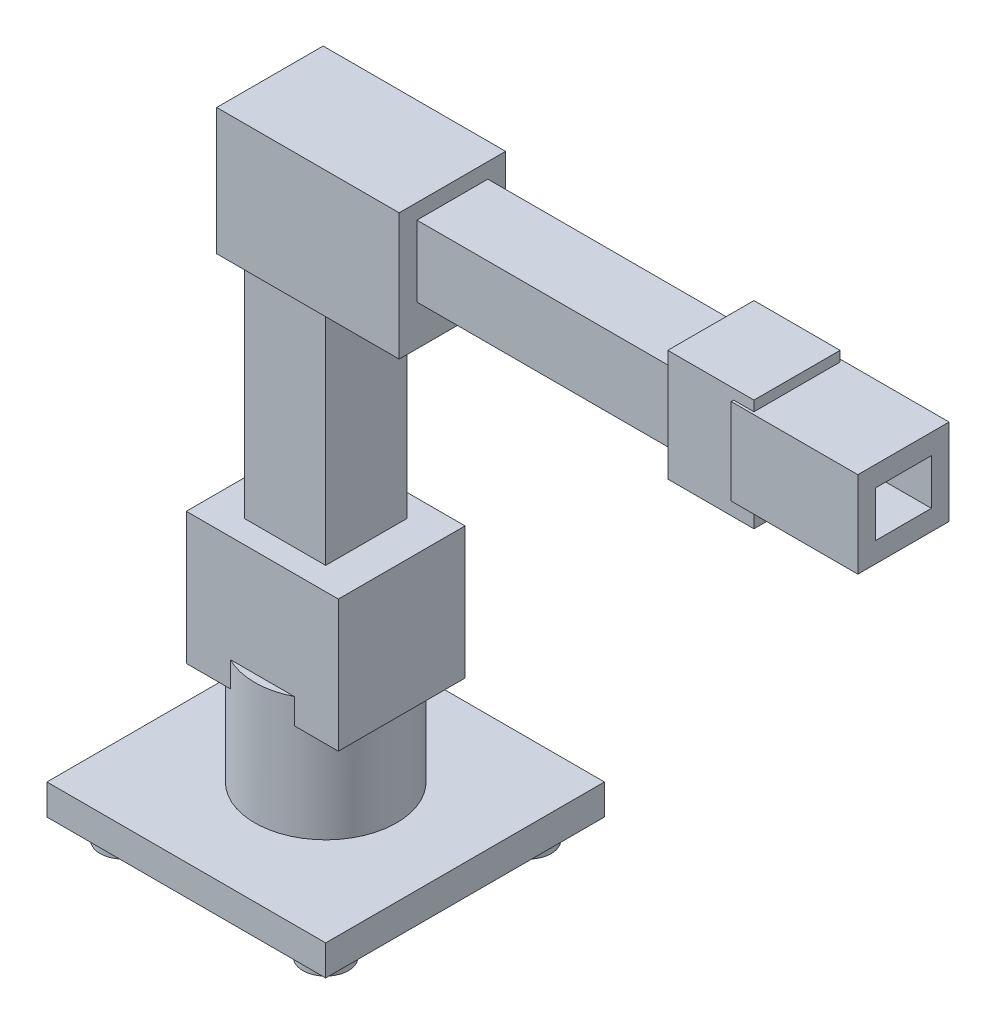
SolidWorks part; units mm, degrees
ref_plane "Front Plane" through (0, 0, 0) normal (0, 0, 1) x (1, 0, 0)
ref_plane "Top Plane" through (0, 0, 0) normal (0, 1, 0) x (1, 0, 0)
ref_plane "Right Plane" through (0, 0, 0) normal (1, 0, 0) x (0, 0, -1)
sketch "Sketch1" plane through (0, 0, 0) normal (0, 1, 0) x (1, 0, 0)
  line L1 (-55, -55) -> (55, -55)
  line L2 (-55, -55) -> (-55, 55)
  line L3 (-55, 55) -> (55, 55)
  line L4 (55, -55) -> (55, 55)
extrude "Boss-Extrude1" add sketch "Sketch1" along normal blind 12
sketch "Sketch2" plane through (0, 0, 0) normal (0, 1, 0) x (1, 0, 0)
  circle A0 centre (-40, -40) radius 9
  circle A1 centre (40, -40) radius 9
  circle A2 centre (-40, 40) radius 9
  circle A3 centre (40, 40) radius 9
extrude "Boss-Extrude2" add sketch "Sketch2" against normal blind 8
sketch "Sketch3" plane through (0, 0, 0) normal (0, 1, 0) x (1, 0, 0)
  circle A0 centre (0, 0) radius 28
extrude "Boss-Extrude3" add sketch "Sketch3" along normal blind 60
sketch "Sketch4" plane through (0, 0, 0) normal (0, 0, 1) x (1, 0, 0)
  line L1 (-30, 50) -> (30, 50)
  line L2 (-30, 50) -> (-30, 102)
  line L3 (-30, 102) -> (30, 102)
  line L4 (30, 50) -> (30, 102)
extrude "Boss-Extrude4" add sketch "Sketch4" along normal mid plane 50
sketch "Sketch5" plane through (0, 0, 0) normal (0, 0, 1) x (1, 0, 0)
  line L1 (-16, 98) -> (16, 98)
  line L2 (-16, 98) -> (-16, 205)
  line L3 (-16, 205) -> (16, 205)
  line L4 (16, 98) -> (16, 205)
extrude "Boss-Extrude5" add sketch "Sketch5" along normal mid plane 32
sketch "Sketch6" plane through (0, 0, 0) normal (0, 0, 1) x (1, 0, 0)
  line L1 (-22, 192) -> (50, 192)
  line L2 (-22, 192) -> (-22, 242)
  line L3 (-22, 242) -> (50, 242)
  line L4 (50, 192) -> (50, 242)
extrude "Boss-Extrude6" add sketch "Sketch6" along normal mid plane 42
sketch "Sketch7" plane through (0, 0, 0) normal (0, 0, 1) x (1, 0, 0)
  circle A0 centre (14, 217) radius 18
extrude "Boss-Extrude7" add sketch "Sketch7" along normal mid plane 12
sketch "Sketch8" plane through (0, 0, 0) normal (0, 0, 1) x (1, 0, 0)
  line L1 (45, 208) -> (160, 208)
  line L2 (45, 208) -> (45, 236)
  line L3 (45, 236) -> (160, 236)
  line L4 (160, 208) -> (160, 236)
extrude "Boss-Extrude8" add sketch "Sketch8" along normal mid plane 28
sketch "Sketch9" plane through (0, 0, 0) normal (0, 0, 1) x (1, 0, 0)
  line L1 (152, 200) -> (186, 200)
  line L2 (152, 200) -> (152, 244)
  line L3 (152, 244) -> (186, 244)
  line L4 (186, 200) -> (186, 244)
extrude "Boss-Extrude9" add sketch "Sketch9" along normal mid plane 34
sketch "Sketch10" plane through (0, 0, 0) normal (0, 0, 1) x (1, 0, 0)
  circle A0 centre (186, 222) radius 13
extrude "Boss-Extrude10" add sketch "Sketch10" along normal mid plane 30
sketch "Sketch11" plane through (0, 0, 0) normal (0, 0, 1) x (1, 0, 0)
  line L1 (178, 206) -> (228, 206)
  line L2 (178, 206) -> (178, 240)
  line L3 (178, 240) -> (228, 240)
  line L4 (228, 206) -> (228, 240)
extrude "Boss-Extrude11" add sketch "Sketch11" along normal mid plane 36
sketch "Sketch12" plane through (0, 0, 0) normal (0, 0, 1) x (1, 0, 0)
  line L1 (196, 214) -> (232, 214)
  line L2 (196, 214) -> (196, 232)
  line L3 (196, 232) -> (232, 232)
  line L4 (232, 214) -> (232, 232)
extrude "Cut-Extrude1" cut sketch "Sketch12" against normal mid plane 22
sketch "Sketch13" plane through (0, 0, 0) normal (1, 0, 0) x (0, 0, -1)
  circle A0 centre (0, 76) radius 6
extrude "Cut-Extrude2" cut sketch "Sketch13" against normal through all
sketch "Sketch14" plane through (0, 0, 0) normal (0, 0, 1) x (1, 0, 0)
  circle A0 centre (14, 217) radius 5
extrude "Cut-Extrude3" cut sketch "Sketch14" against normal through all
sketch "Sketch15" plane through (0, 0, 0) normal (0, 0, 1) x (1, 0, 0)
  circle A0 centre (169, 222) radius 4
extrude "Cut-Extrude4" cut sketch "Sketch15" against normal through all
sketch "Sketch16" plane through (0, 0, 0) normal (0, 1, 0) x (1, 0, 0)
  circle A0 centre (-42, -42) radius 3.5
  circle A1 centre (42, -42) radius 3.5
  circle A2 centre (-42, 42) radius 3.5
  circle A3 centre (42, 42) radius 3.5
extrude "Cut-Extrude5" cut sketch "Sketch16" against normal through all
